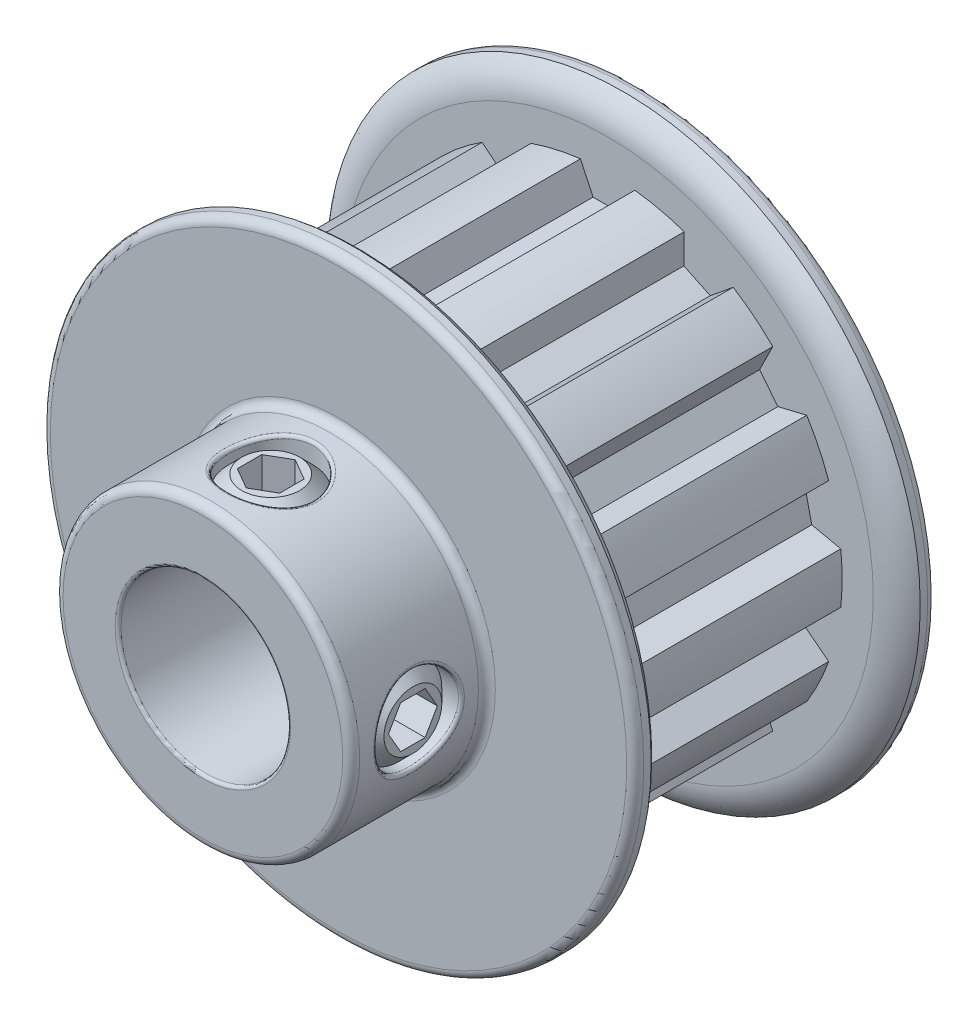
SolidWorks part; units mm, degrees
ref_plane "Front Plane" through (0, 0, 0) normal (0, 0, 1) x (1, 0, 0)
ref_plane "Top Plane" through (0, 0, 0) normal (0, 1, 0) x (1, 0, 0)
ref_plane "Right Plane" through (0, 0, 0) normal (1, 0, 0) x (0, 0, -1)
sketch "Sketch1" plane through (0, 0, 0) normal (0, 0, 1) x (1, 0, 0)
  line L0 (-1.2827, 10.9903) -> (-0.6905, 9.7203)
  line L1 (-0.6905, 9.7203) -> (0.6905, 9.7203)
  line L2 (0.6905, 9.7203) -> (1.2827, 10.9903)
  line L3 (-1.2827, 10.9903) -> (1.2827, 10.9903)
  line L4 (0, 0) -> (0, 9.7203) construction
  line L5 (0, 9.7203) -> (0, 12.0063) construction
  circle A0 centre (0, 0) radius 11.3 construction
  circle A1 centre (0, 0) radius 14 construction
  circle A2 centre (0, 0) radius 11.0649 construction
  point P6 (0, 10.9903)
  point P11 (0, 11.3)
  point P13 (0, 14)
  point P14 (0, 11.0649)
  dimension "Pitch Diameter" = 22.6
  dimension "OD" = 28
  dimension "D5" = 50
  dimension "D6" = 2.5654
  dimension "D4" = 1.27
  dimension "D3" = 2.286
  dimension "D2" = 0.7063
sketch "Sketch2" plane through (0, 0, 0) normal (1, 0, 0) x (0, 0, -1)
  line L0 (-10.3, 4) -> (10.3, 4) construction
  line L1 (-10.3, 4) -> (-10.3, 7) construction
  line L2 (-10.3, 7) -> (-3.9, 7) construction
  line L3 (-3.9, 7) -> (-3.9, 14) construction
  line L4 (-3.9, 14) -> (-2.4, 14) construction
  line L5 (-2.4, 14) -> (-2.4, 11.0649) construction
  line L6 (-2.4, 11.0649) -> (8.8, 11.0649) construction
  line L7 (8.8, 11.0649) -> (8.8, 14) construction
  line L8 (8.8, 14) -> (10.3, 14) construction
  line L9 (10.3, 14) -> (10.3, 4) construction
  line L10 (-10.3, 0) -> (10.3, 0) construction
  line L13 (-3.9, 14) -> (-3.15, 14) construction
  line L14 (-2.4, 12.5324) -> (-2.4, 11.0649) construction
  line L15 (8.8, 11.0649) -> (8.8, 12.5324) construction
  line L16 (9.55, 14) -> (10.3, 14) construction
  arc A0 (-2.4, 12.5324) -> (-3.15, 14) centre (-4.2109, 12.5324) ccw construction
  arc A1 (8.8, 12.5324) -> (9.55, 14) centre (10.6109, 12.5324) cw construction
  point P12 (-2.4, 12.5324)
  point P14 (-3.15, 14)
  point P20 (8.8, 12.5324)
  point P21 (9.55, 14)
  point P25 (8.8, 0)
  point P26 (-2.4, 0)
  dimension "Overall Width" = 20.6
  dimension "Outside Width" = 14.2
  dimension "Inside Width" = 11.2
  dimension "Hub Diameter" = 14
  dimension "For Shaft Diameter" = 8
sketch "Sketch7" plane through (0, 0, 0) normal (1, 0, 0) x (0, 0, -1)
  line L0 (-10.3, 4) -> (-10.3, 7) construction
  line L1 (-10.3, 7) -> (-3.9, 7) construction
  line L2 (-3.9, 7) -> (-3.9, 14) construction
  line L3 (-3.9, 14) -> (-3.15, 14) construction
  line L4 (-2.4, 12.5324) -> (-2.4, 11.0649) construction
  line L5 (-2.4, 11.0649) -> (8.8, 11.0649) construction
  line L6 (8.8, 11.0649) -> (8.8, 12.5324) construction
  line L7 (9.55, 14) -> (10.3, 14) construction
  line L8 (10.3, 14) -> (10.3, 4) construction
  line L9 (-10.3, 4) -> (10.3, 4) construction
  line L10 (-10.3, 4) -> (-10.3, 7)
  line L11 (-10.3, 7) -> (-3.9, 7)
  line L12 (-3.9, 7) -> (-3.9, 14)
  line L13 (-3.9, 14) -> (-3.15, 14)
  line L14 (-2.4, 12.5324) -> (-2.4, 11.0649)
  line L15 (-2.4, 11.0649) -> (8.8, 11.0649)
  line L16 (8.8, 11.0649) -> (8.8, 12.5324)
  line L17 (9.55, 14) -> (10.3, 14)
  line L18 (10.3, 14) -> (10.3, 4)
  line L19 (-10.3, 4) -> (10.3, 4)
  arc A0 (-2.4, 12.5324) -> (-3.15, 14) centre (-4.2109, 12.5324) ccw construction
  arc A1 (9.55, 14) -> (8.8, 12.5324) centre (10.6109, 12.5324) ccw construction
  arc A2 (-2.4, 12.5324) -> (-3.15, 14) centre (-4.2109, 12.5324) ccw
  arc A3 (9.55, 14) -> (8.8, 12.5324) centre (10.6109, 12.5324) ccw
revolve "Revolve1" add sketch "Sketch7" angle 360 about L10
sketch "Sketch3" plane through (0, 0, 0) normal (0, 0, 1) x (1, 0, 0)
  line L0 (-0.6905, 9.7203) -> (0.6905, 9.7203) construction
  line L1 (0.6905, 9.7203) -> (1.2827, 10.9903) construction
  line L2 (-1.2827, 10.9903) -> (-0.6905, 9.7203) construction
  line L3 (-0.6905, 9.7203) -> (0.6905, 9.7203)
  line L4 (0.6905, 9.7203) -> (1.2827, 10.9903)
  line L5 (-1.2827, 10.9903) -> (-0.6905, 9.7203)
  arc A1 (1.2827, 10.9903) -> (-1.2827, 10.9903) centre (0, 0) ccw
  circle A2 centre (0, 0) radius 11.0649 construction
extrude "Cut-Extrude1" cut sketch "Sketch3" against normal up to vertex (8.8 mm away) from vertex at 2.4 starting at point (0, 11.0649, 2.4)
pattern_circular "CirPattern1" count 14 over 360 about axis through (0, 0, 0) along (0, 0, 1) of "Cut-Extrude1"
sketch "Sketch4" plane through (0, 0, 0) normal (0, 1, 0) x (1, 0, 0)
  line L0 (0, -3.9) -> (0, -10.3) construction
  line L3 (0, -10.3) -> (0, 10.3) construction
  line L4 (-7, -3.9) -> (7, -3.9) construction
  line L5 (-7, -10.3) -> (7, -10.3) construction
  circle A0 centre (0, -7.1) radius 2
  dimension "D1" = 4
extrude "Cut-Extrude2" cut sketch "Sketch4" along normal through all
ref_plane "Plane1" through (0, 0, 7.1) normal (0, 0, 1) x (1, 0, 0)
sketch "Sketch5" plane through (0, 0, 7.1) normal (0, 0, 1) x (1, 0, 0)
  line L0 (0, 0) -> (0, 7) construction
  line L1 (-2, 6.7082) -> (-2, 3.4641) construction
  line L2 (-2, 6.7082) -> (-2, 3.4641) construction
  line L3 (0, 6.7082) -> (0, 4)
  line L4 (0, 4) -> (-1.365, 4)
  line L5 (-2, 6.0732) -> (-2, 4.635)
  line L6 (-1.365, 6.7082) -> (0, 6.7082)
  line L7 (-2, 6.0732) -> (-1.365, 6.7082)
  line L8 (-2, 4.635) -> (-1.365, 4)
  line L9 (0, 14) -> (0, 4) construction
  line L10 (0, 4) -> (0, 7) construction
  point P13 (-2, 4)
  point P15 (-2, 6.7082)
revolve "Revolve2" add sketch "Sketch5" angle 360 mid plane about L0
sketch "Sketch6" plane through (0, 6.7082, 0) normal (0, -1, 0) x (-1, 0, 0)
  line L1 (0, -5.9453) -> (-1, -6.5226)
  line L2 (-1, -6.5226) -> (-1, -7.6774)
  line L3 (-1, -7.6774) -> (0, -8.2547)
  line L4 (0, -8.2547) -> (1, -7.6774)
  line L5 (1, -7.6774) -> (1, -6.5226)
  line L6 (1, -6.5226) -> (0, -5.9453)
  circle A0 centre (0, -7.1) radius 1 construction
  dimension "D1" = 2
extrude "Cut-Extrude3" cut sketch "Sketch6" along normal blind 1.5
pattern_circular "CirPattern2" count 2 every 90 about axis through (0, 0, 0) along (0, 0, 1) of "Cut-Extrude2", "Revolve2", "Cut-Extrude3"
fillet "Fillet1" radius 0.4 4 edges at (14, 0, -10.3) (14, 0, 3.9) (7, 0, 3.9) (7, 0, 10.3)
fillet "Fillet2" radius 0.14 4 edges at (4, 0, 10.3) (6.9902, -0.3708, 9.0653) (0.3708, 6.9902, 9.0653) (4, 0, -10.3)
equation "\"D1@Sketch4\" = \"For Shaft Diameter@Sketch2\"/2"
equation "\"D1@Sketch6\" = \"D1@Sketch4\"/2"
equation "\"D1@Cut-Extrude3\" = \"D1@Sketch6\"*.75"
equation "\"D1@Fillet1\"=\"Hub Diameter@Sketch2\" / 35"
equation "\"D2@Sketch1\"=\"Pitch Diameter@Sketch1\"/32"
equation "\"D1@Fillet2\"=\"Hub Diameter@Sketch2\"*.01"
